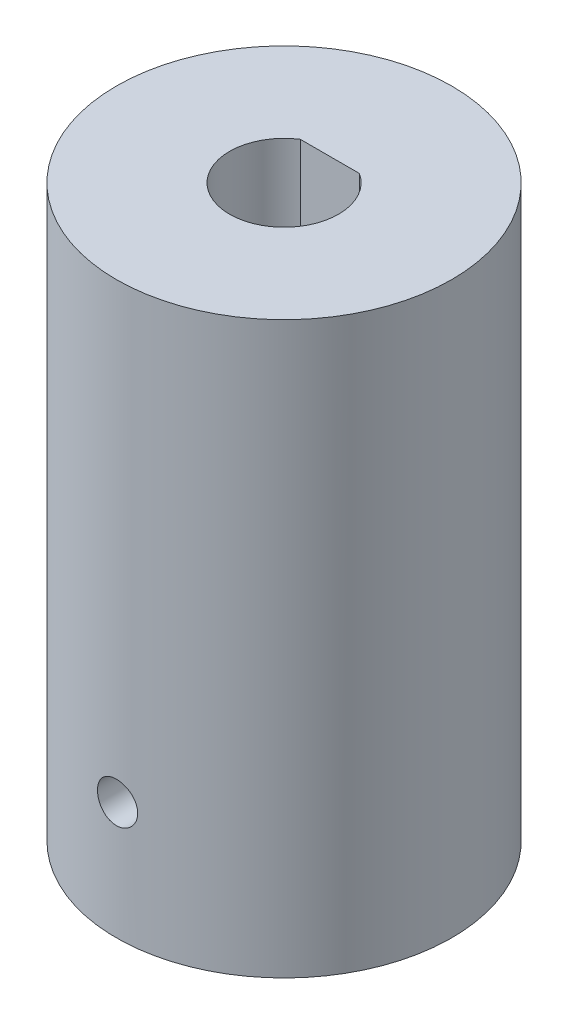
SolidWorks part; units mm, degrees
ref_plane "Front Plane" through (0, 0, 0) normal (0, 0, 1) x (1, 0, 0)
ref_plane "Top Plane" through (0, 0, 0) normal (0, 1, 0) x (1, 0, 0)
ref_plane "Right Plane" through (0, 0, 0) normal (1, 0, 0) x (0, 0, -1)
sketch "Sketch1" plane through (0, 0, 0) normal (0, 1, 0) x (1, 0, 0)
  circle A0 centre (0, 0) radius 12.7
  dimension "D1" = 25.4
extrude "Boss-Extrude1" add sketch "Sketch1" along normal blind 50.8
sketch "Sketch4" plane through (0, 0, 0) normal (0, -1, 0) x (1, 0, 0)
  circle A0 centre (0, 0) radius 6.35
  dimension "D1" = 12.7
extrude "Cut-Extrude2" cut sketch "Sketch4" against normal blind 33.02
sketch "Sketch5" plane through (0, 0, 0) normal (0, 0, 1) x (1, 0, 0)
  circle A0 centre (0, 16.51) radius 1.524
  dimension "D1" = 3.048
  dimension "D2" = 16.51
extrude "Cut-Extrude3" cut sketch "Sketch5" against normal through all both and the other way through all
sketch "Sketch6" plane through (0, 50.8, 0) normal (0, 1, 0) x (1, 0, 0)
  line L0 (-2.2388, 3.4676) -> (2.2388, 3.4676)
  arc A0 (-2.2388, 3.4676) -> (2.2388, 3.4676) centre (0, 0) ccw
  dimension "D1" = 8.255
  dimension "D2" = 4.4775
extrude "Cut-Extrude4" cut sketch "Sketch6" against normal blind 15.24
sketch "Sketch7" plane through (0, 0, 0) normal (0, 0, 1) x (1, 0, 0)
  line L1 (12.7, 50.8) -> (-12.7, 50.8) construction
  circle A0 centre (0, 43.18) radius 1.9939
  dimension "D1" = 3.9878
  dimension "D2" = 7.62
extrude "Cut-Extrude5" cut sketch "Sketch7" against normal blind 15.24
sketch "Sketch8" plane through (0, 0, 0) normal (0, -1, 0) x (1, 0, 0)
  circle A0 centre (0, 0) radius 14.2875
  dimension "D1" = 28.575
extrude "Cut-Extrude6" cut sketch "Sketch8" against normal blind 7.62
equation "\"D2@Sketch6\"=\"D1@Sketch6\"*.5424"
